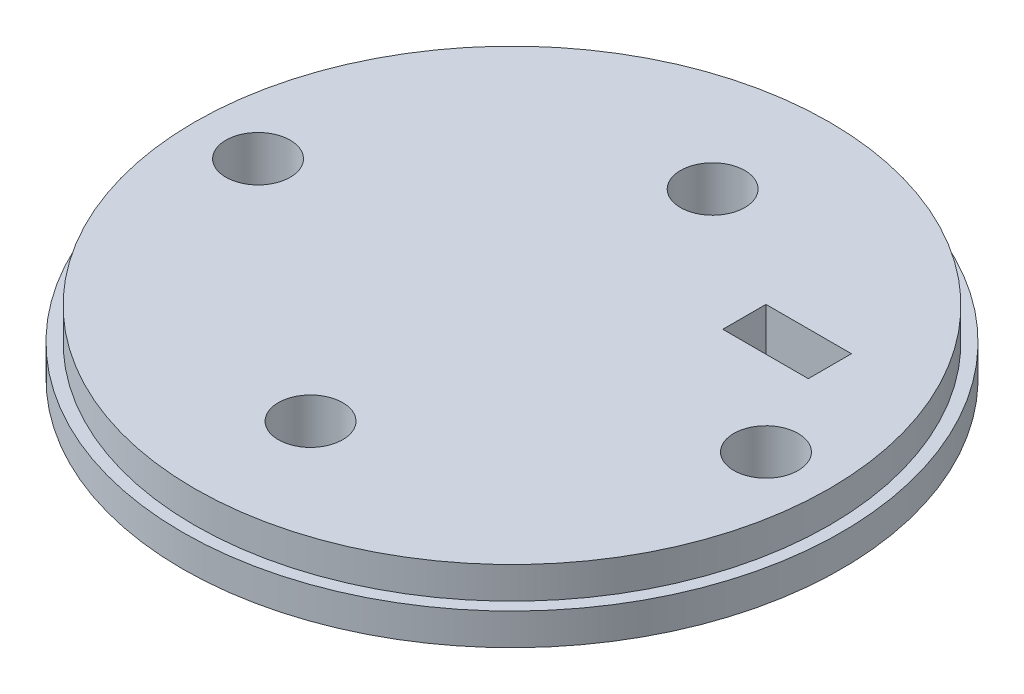
SolidWorks part; units mm, degrees
material "6061 Alloy"
ref_plane "Front Plane" through (0, 0, 0) normal (0, 0, 1) x (1, 0, 0)
ref_plane "Top Plane" through (0, 0, 0) normal (0, 1, 0) x (1, 0, 0)
ref_plane "Right Plane" through (0, 0, 0) normal (1, 0, 0) x (0, 0, -1)
sketch "Sketch1" plane through (0, 0, 0) normal (0, 1, 0) x (1, 0, 0)
  circle A0 centre (0, 0) radius 49.4411
  dimension "D1" = 98.8822
extrude "Boss-Extrude2" add sketch "Sketch1" along normal blind 9.525
sketch "Sketch4" plane through (0, 9.525, 0) normal (0, 1, 0) x (1, 0, 0)
  circle A0 centre (0, 0) radius 47.625
  circle A1 centre (0, 0) radius 50.546
  dimension "D1" = 95.25
extrude "Cut-Extrude2" cut sketch "Sketch4" against normal blind 4.7625
sketch "Sketch5" plane through (0, 0, 0) normal (0, -1, 0) x (1, 0, 0)
  line L0 (0, -25.4) -> (0, 25.4) construction
  line L1 (0, 0) -> (90.4122, 0) construction
  line L2 (4.7625, -25.4) -> (4.7625, 25.4)
  line L3 (0, 0) -> (-38.1, 0) construction
  circle A3 centre (-0.0635, 30.1621) radius 4.826
  circle A4 centre (-0.0635, -30.1621) radius 4.826
  circle A5 centre (-38.1, 0) radius 4.826
  circle A6 centre (38.1, 0) radius 4.826
  dimension "D2" = 4.7625
  dimension "D4" = 9.652
  dimension "D5" = 38.1
  dimension "D6" = 9.652
  dimension "D1" = 25.4
  dimension "D3" = 4.7625
extrude "Cut-Extrude4" cut sketch "Sketch5" against normal through all both and the other way through all contours A3 | A4 | A5 | A6
sketch "Sketch6" plane through (0, 9.525, 0) normal (0, 1, 0) x (1, 0, 0)
  line L0 (0, 0) -> (31.75, 0)
  line L1 (31.75, 0) -> (31.75, 19.177)
  line L3 (31.75, 19.177) -> (18.923, 19.177)
  line L4 (31.75, 19.177) -> (31.75, 12.7)
  line L5 (31.75, 12.7) -> (18.923, 12.7)
  line L6 (18.923, 19.177) -> (18.923, 12.7)
  dimension "D1" = 31.75
  dimension "D2" = 19.177
  dimension "D3" = 12.827
  dimension "D4" = 6.477
extrude "Cut-Extrude5" cut sketch "Sketch6" against normal through all both and the other way through all contours L4 L3 L6 L5
